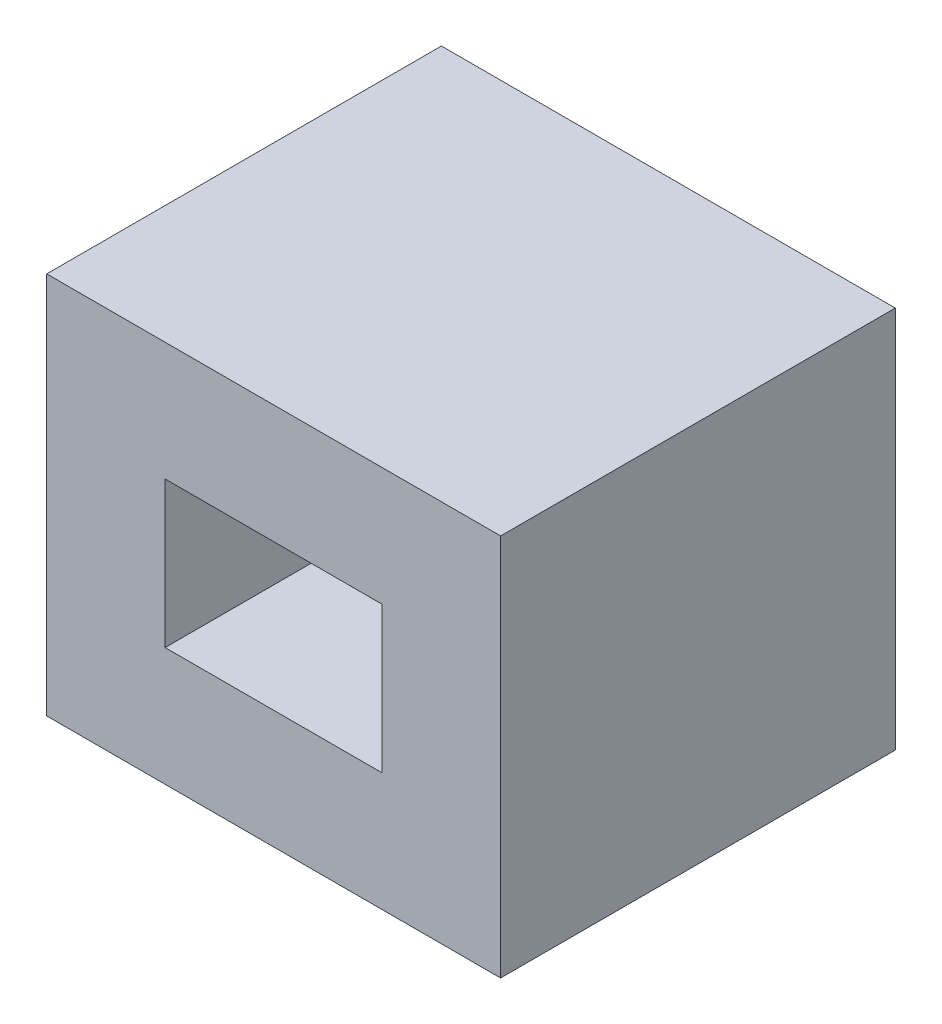
SolidWorks part; units mm, degrees
ref_plane "Front Plane" through (0, 0, 0) normal (0, 0, 1) x (1, 0, 0)
ref_plane "Top Plane" through (0, 0, 0) normal (0, 1, 0) x (1, 0, 0)
ref_plane "Right Plane" through (0, 0, 0) normal (1, 0, 0) x (0, 0, -1)
sketch "Sketch1" plane through (0, 0, 0) normal (0, 0, 1) x (1, 0, 0)
  line L1 (-5.75, 4.85) -> (5.75, 4.85)
  line L2 (-5.75, 4.85) -> (-5.75, -4.85)
  line L3 (-5.75, -4.85) -> (5.75, -4.85)
  line L4 (5.75, 4.85) -> (5.75, -4.85)
  line L6 (2.75, -1.85) -> (-2.75, -1.85)
  line L7 (2.75, -1.85) -> (2.75, 1.85)
  line L8 (2.75, 1.85) -> (-2.75, 1.85)
  line L9 (-2.75, -1.85) -> (-2.75, 1.85)
  point P4 (0, 1.85)
  point P9 (0, 4.85)
  point P11 (-2.75, 0)
  point P12 (-5.75, 0)
  dimension "D1" = 5.5
  dimension "D2" = 3.7
  dimension "D3" = 3
  dimension "D4" = 3
extrude "Boss-Extrude1" add sketch "Sketch1" along normal blind 10
